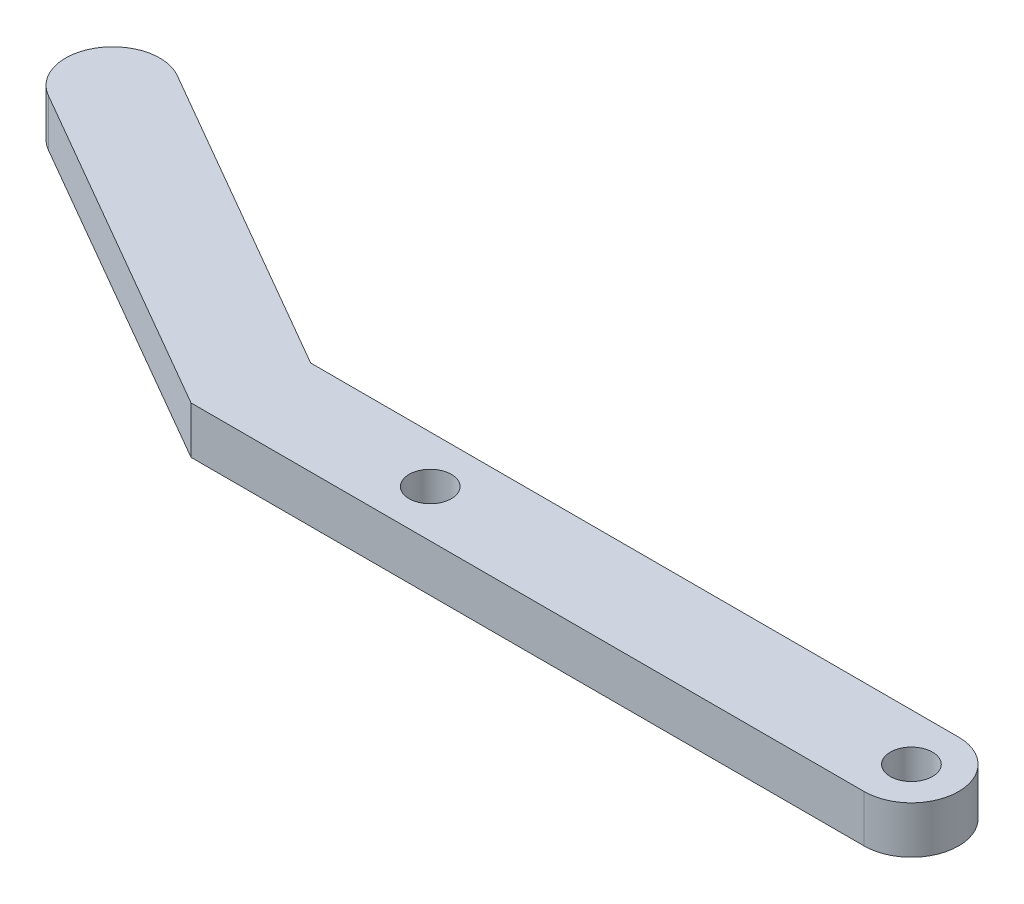
SolidWorks part; units mm, degrees
ref_plane "Front" through (0, 0, 0) normal (0, 0, 1) x (1, 0, 0)
ref_plane "Top" through (0, 0, 0) normal (0, 1, 0) x (1, 0, 0)
ref_plane "Right" through (0, 0, 0) normal (1, 0, 0) x (0, 0, -1)
sketch "Sketch1" plane through (0, 0, 0) normal (0, 1, 0) x (1, 0, 0)
  line L0 (-22.225, 0) -> (22.225, 0) construction
  line L1 (-21.3743, 3.175) -> (22.225, 3.175)
  line L2 (-21.3743, 3.175) -> (-42.6345, 15.4496)
  line L3 (-22.225, 0) -> (-44.222, 12.7) construction
  line L4 (-23.0757, -3.175) -> (22.225, -3.175)
  line L5 (-23.0757, -3.175) -> (-45.8095, 9.9504)
  circle A0 centre (22.225, 0) radius 1.4224
  circle A1 centre (-10.1549, 0) radius 1.4224
  arc A2 (22.225, 3.175) -> (22.225, -3.175) centre (22.225, 0) cw
  arc A3 (-42.6345, 15.4496) -> (-45.8095, 9.9504) centre (-44.222, 12.7) ccw
  dimension "D2" = 2.8448
  dimension "D3" = 2.8448
  dimension "D1" = 44.45
  dimension "D4" = 32.3799
  dimension "D5" = 150
  dimension "D6" = 25.4
  dimension "D7" = 3.175
  dimension "D8" = 3.175
extrude "Boss-Extrude1" add sketch "Sketch1" along normal blind 3.175
